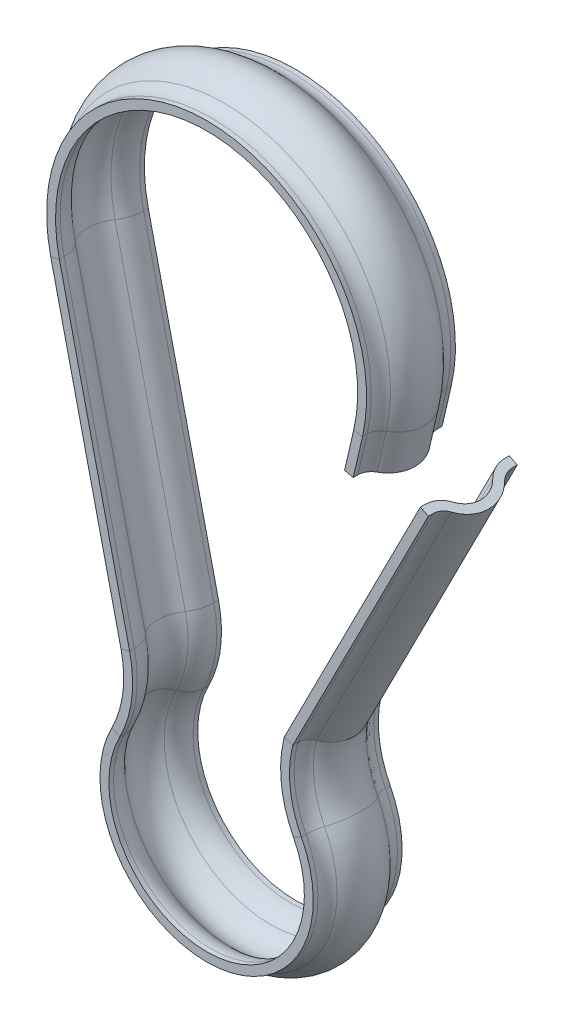
SolidWorks part; units mm, degrees
material "AISI 316 Stainless Steel Sheet (SS)"
ref_plane "Front Plane" through (0, 0, 0) normal (0, 0, 1) x (1, 0, 0)
ref_plane "Top Plane" through (0, 0, 0) normal (0, 1, 0) x (1, 0, 0)
ref_plane "Right Plane" through (0, 0, 0) normal (1, 0, 0) x (0, 0, -1)
sketch "Sketch1" plane through (0, 0, 0) normal (0, 0, 1) x (1, 0, 0)
  line L0 (9.2241, -4.5) -> (9.7437, -2.2495)
  line L1 (-9.7437, -2.2495) -> (-5.791, -19.3704)
  line L2 (5.791, -19.3704) -> (13.3679, -4.5)
  arc A0 (9.7437, -2.2495) -> (-9.7437, -2.2495) centre (0, 0) ccw
  arc A1 (-5.791, -19.3704) -> (-6.22, -22.7889) centre (-10.6629, -20.4952) cw
  arc A2 (-6.22, -22.7889) -> (6.22, -22.7889) centre (0, -26) ccw
  arc A3 (6.22, -22.7889) -> (5.791, -19.3704) centre (10.6629, -20.4952) cw
  point P11 (0, 0)
  point P13 (9.8494, -2.4013)
  point P15 (0, 0)
  point P16 (-8.6376, -26.9064)
  point P17 (9.542, -4.8471)
  point P18 (0, 0)
  point P19 (22.3324, -4.5)
  point P20 (21.6218, -6.5221)
  point P21 (0, 0)
  point P22 (9.2014, -4.5)
  point P23 (0, 0)
  point P24 (0, 0)
  dimension "D2" = 14
  dimension "D1" = 10
  dimension "D6" = 5
  dimension "D7" = 5
  dimension "D9" = 7
  dimension "D3" = 4.5
  dimension "D4" = 26
  dimension "D5" = 4.5
  dimension "D8" = 26
sketch "Sketch2" plane through (0, 0, 0) normal (1, 0, 0) x (0, 0, -1)
  line L0 (-2.5, 9) -> (-2.2361, 9)
  line L1 (2.2361, 9) -> (2.5, 9)
  line L2 (-2.5, 8.5) -> (-2.2361, 8.5)
  line L3 (2.2361, 8.5) -> (2.5, 8.5)
  line L4 (0, 0) -> (0, 10) construction
  line L5 (0, 10) -> (0, -2.2495) construction
  line L6 (0, 10) -> (7.2359, 10) construction
  line L7 (2.5, 9) -> (2.5, 8.5)
  line L8 (-2.5, 9) -> (-2.5, 8.5)
  arc A0 (-1.4907, 9.3333) -> (1.4907, 9.3333) centre (0, 8) cw
  arc A1 (1.4907, 9.3333) -> (2.2361, 9) centre (2.2361, 10) ccw
  arc A2 (-2.2361, 9) -> (-1.4907, 9.3333) centre (-2.2361, 10) ccw
  arc A3 (-2.2361, 8.5) -> (-1.118, 9) centre (-2.2361, 10) ccw
  arc A4 (-1.118, 9) -> (1.118, 9) centre (0, 8) cw
  arc A5 (1.118, 9) -> (2.2361, 8.5) centre (2.2361, 10) ccw
  point P7 (0, 10)
  point P14 (1.7321, 9)
  point P17 (-1.7321, 9)
  dimension "D2" = 5
  dimension "D3" = 2
  dimension "D5" = 1
  dimension "D1" = 10
  dimension "D4" = 1
  dimension "D6" = 0.5
sweep "Sweep1" add profiles "Sketch2" path "Sketch1"
